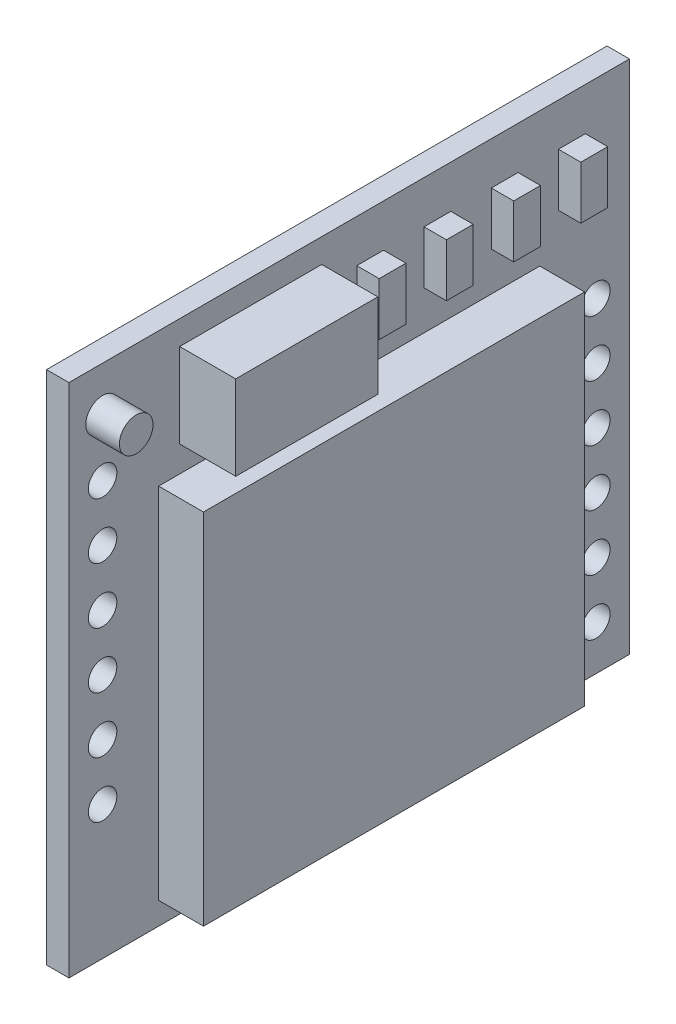
SolidWorks part; units mm, degrees
ref_plane "Front Plane" through (0, 0, 0) normal (0, 0, 1) x (1, 0, 0)
ref_plane "Top Plane" through (0, 0, 0) normal (0, 1, 0) x (1, 0, 0)
ref_plane "Right Plane" through (0, 0, 0) normal (1, 0, 0) x (0, 0, -1)
sketch "Sketch1" plane through (0, 0, 0) normal (1, 0, 0) x (0, 0, -1)
  line L1 (0, 0) -> (25, 0)
  line L2 (0, 0) -> (0, -23)
  line L3 (0, -23) -> (25, -23)
  line L4 (25, 0) -> (25, -23)
  dimension "D1" = 25
  dimension "D2" = 23
extrude "Boss-Extrude1" add sketch "Sketch1" along normal blind 1
sketch "Sketch2" plane through (1, 0, 0) normal (1, 0, 0) x (0, 0, -1)
  line L0 (25, 0) -> (0, 0) construction
  line L1 (4, -6) -> (21, -6)
  line L2 (4, -6) -> (4, -22)
  line L3 (4, -22) -> (21, -22)
  line L4 (21, -6) -> (21, -22)
  line L5 (25, -23) -> (25, 0) construction
  line L6 (0, 0) -> (0, -23) construction
  line L7 (0, -23) -> (25, -23) construction
  dimension "D1" = 6
  dimension "D2" = 4
  dimension "D3" = 4
  dimension "D4" = 1
extrude "Boss-Extrude2" add sketch "Sketch2" along normal blind 2
sketch "Sketch3" plane through (1, 0, 0) normal (1, 0, 0) x (0, 0, -1)
  line L1 (4.9389, -1.0767) -> (11.2755, -1.0767)
  line L2 (4.9389, -1.0767) -> (4.9389, -4.8419)
  line L3 (4.9389, -4.8419) -> (11.2755, -4.8419)
  line L4 (11.2755, -1.0767) -> (11.2755, -4.8419)
extrude "Boss-Extrude3" add sketch "Sketch3" along normal blind 2.5
sketch "Sketch4" plane through (1, 0, 0) normal (1, 0, 0) x (0, 0, -1)
  line L0 (15.8367, -1.9032) -> (15.8367, -4.2603)
  line L1 (12.8367, -1.9032) -> (14.0306, -1.9032)
  line L2 (12.8367, -1.9032) -> (12.8367, -4.2603)
  line L3 (12.8367, -4.2603) -> (14.0306, -4.2603)
  line L4 (14.0306, -1.9032) -> (14.0306, -4.2603)
  line L5 (15.8367, -1.9032) -> (17.0306, -1.9032)
  line L6 (17.0306, -1.9032) -> (17.0306, -4.2603)
  line L7 (15.8367, -4.2603) -> (17.0306, -4.2603)
  line L8 (18.8367, -1.9032) -> (18.8367, -4.2603)
  line L9 (18.8367, -1.9032) -> (20.0306, -1.9032)
  line L10 (20.0306, -1.9032) -> (20.0306, -4.2603)
  line L11 (18.8367, -4.2603) -> (20.0306, -4.2603)
  dimension "D1" = 3
extrude "Boss-Extrude4" add sketch "Sketch4" along normal blind 1
sketch "Sketch5" plane through (1, 0, 0) normal (1, 0, 0) x (0, 0, -1)
  line L0 (20.0306, -1.9032) -> (18.8367, -1.9032) construction
  line L1 (23.0306, -1.9032) -> (21.8306, -1.9032)
  line L2 (23.0306, -1.9032) -> (23.0306, -4.2603)
  line L3 (23.0306, -4.2603) -> (21.8306, -4.2603)
  line L4 (21.8306, -1.9032) -> (21.8306, -4.2603)
  line L5 (18.8367, -4.2603) -> (20.0306, -4.2603) construction
  line L6 (20.0306, -4.2603) -> (20.0306, -1.9032) construction
  point P8 (22.4306, -4.2603)
  point P11 (23.0306, -3.0818)
  dimension "D1" = 0
  dimension "D2" = 0
  dimension "D3" = 3
  dimension "D4" = 1.2
extrude "Boss-Extrude5" add sketch "Sketch5" along normal blind 1
sketch "Sketch6" plane through (1, 0, 0) normal (1, 0, 0) x (0, 0, -1)
  line L0 (25, 0) -> (0, 0) construction
  line L1 (0, 0) -> (0, -23) construction
  circle A0 centre (1.5, -2) radius 0.75
  dimension "D1" = 2
  dimension "D2" = 1.5
  dimension "D3" = 1.5
extrude "Boss-Extrude6" add sketch "Sketch6" along normal blind 1.5
sketch "Sketch7" plane through (1, 0, 0) normal (1, 0, 0) x (0, 0, -1)
  line L0 (0, 0) -> (0, -23) construction
  line L1 (25, -23) -> (25, 0) construction
  line L2 (0, -23) -> (25, -23) construction
  circle A0 centre (1.5, -4.54) radius 0.635
  circle A1 centre (1.5, -2) radius 0.75 construction
  circle A2 centre (1.5, -7.04) radius 0.635
  circle A3 centre (1.5, -9.54) radius 0.635
  circle A4 centre (1.5, -12.04) radius 0.635
  circle A5 centre (1.5, -14.54) radius 0.635
  circle A6 centre (1.5, -17.04) radius 0.635
  circle A7 centre (23.5, -21) radius 0.635
  circle A8 centre (23.5, -18.5) radius 0.635
  circle A9 centre (23.5, -16) radius 0.635
  circle A10 centre (23.5, -13.5) radius 0.635
  circle A11 centre (23.5, -11) radius 0.635
  circle A12 centre (23.5, -8.5) radius 0.635
  dimension "D1" = 1.27
  dimension "D2" = 1.5
  dimension "D3" = 2.54
  dimension "D5" = 1.5
  dimension "D6" = 2
  dimension "D7" = 1.27
  dimension "D4" = 6
  dimension "D8" = 6
extrude "Cut-Extrude1" cut sketch "Sketch7" against normal blind 1.5
sketch "Sketch8" plane through (0, 0, 0) normal (-1, 0, 0) x (0, 0, 1)
  line L0 (-25, -23) -> (-25, 0) construction
  line L1 (-20, -5) -> (-5, -5)
  line L2 (-20, -5) -> (-20, -22.5)
  line L3 (-20, -22.5) -> (-5, -22.5)
  line L4 (-5, -5) -> (-5, -22.5)
  line L5 (0, 0) -> (0, -23) construction
  line L6 (-25, 0) -> (0, 0) construction
  line L7 (0, -23) -> (-25, -23) construction
  dimension "D1" = 5
  dimension "D2" = 5
  dimension "D3" = 5
  dimension "D4" = 0.5
extrude "Boss-Extrude7" add sketch "Sketch8" along normal blind 2
